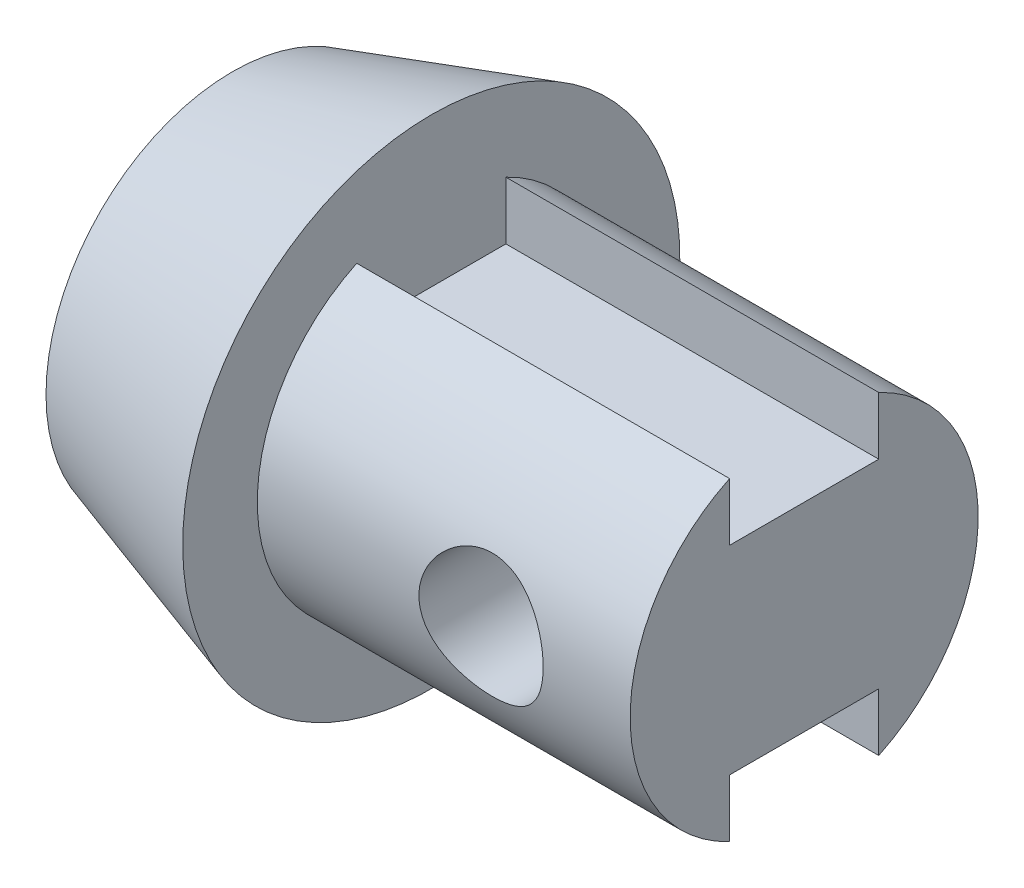
SolidWorks part; units mm, degrees
ref_plane "Front Plane" through (0, 0, 0) normal (1, 0, 0) x (0, 1, 0)
ref_plane "Top Plane" through (0, 0, 0) normal (0, 0, 1) x (0, 1, 0)
ref_plane "Right Plane" through (0, 0, 0) normal (0, 1, 0) x (-1, 0, 0)
sketch "Sketch1" plane through (0, 0, 0) normal (0, 0, 1) x (0, 1, 0)
  line L0 (0, 0) -> (7.5, 0)
  line L1 (7.5, 0) -> (10, -8)
  line L2 (10, -8) -> (7, -8)
  line L3 (7, -8) -> (7, -23)
  line L4 (7, -23) -> (0, -23)
  line L5 (0, -23) -> (0, 0) construction
  line L6 (0, 0) -> (0, -23)
  point P3 (10, -6.5482)
  dimension "D1" = 15
  dimension "D2" = 20
  dimension "D3" = 15
  dimension "D4" = 14
  dimension "D5" = 8
revolve "Revolve1" add sketch "Sketch1" angle 360 about L5
sketch "Sketch2" plane through (23, 0, 0) normal (1, 0, 0) x (0, 1, 0)
  line L1 (7, 3) -> (4, 3)
  line L2 (7, 3) -> (7, -3)
  line L3 (7, -3) -> (4, -3)
  line L4 (4, 3) -> (4, -3)
  line L5 (-7, 3) -> (-4, 3)
  line L6 (-7, 3) -> (-7, -3)
  line L7 (-7, -3) -> (-4, -3)
  line L8 (-4, 3) -> (-4, -3)
  circle A1 centre (0, 0) radius 7
  circle A2 centre (0, 0) radius 7
  point P11 (4, 0)
  point P13 (8.3236, 2.2477)
  circle M10 centre (0, 0) radius 7
  dimension "D2" = 6
  dimension "D3" = 8
  dimension "D1" = 0
extrude "Cut-Extrude1" cut sketch "Sketch2" against normal up to surface (15 mm away) and the other way through all contours L1 L4 L3 M10 | L8 L5 L7 M10 up to face at (8, 10, 0)
sketch "Sketch3" plane through (0, 0, 0) normal (0, 0, 1) x (0, 1, 0)
  line L0 (-6.3246, -23) -> (6.3246, -23) construction
  circle A0 centre (0, -17) radius 2.5
  point P2 (0, 0)
  dimension "D1" = 5
  dimension "D2" = 6
extrude "Cut-Extrude2" cut sketch "Sketch3" against normal through all both and the other way through all
